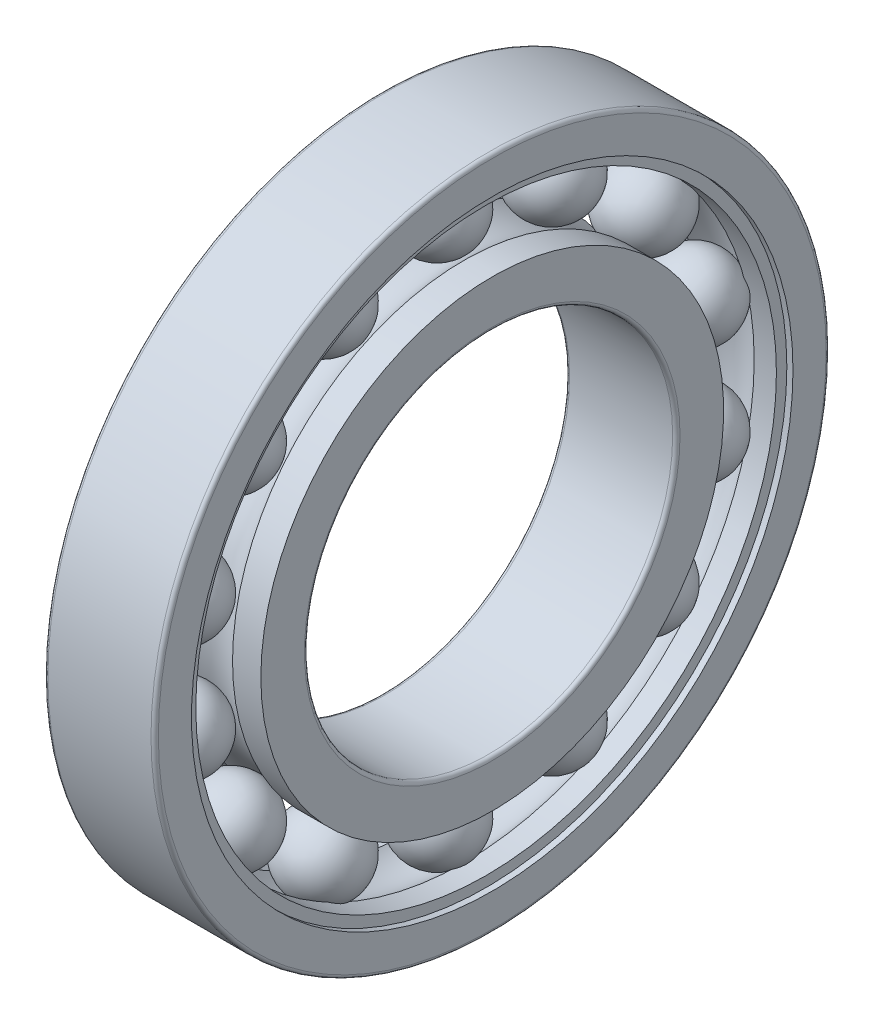
SolidWorks part; units mm, degrees
ref_plane "Front Plane" through (0, 0, 0) normal (0, 0, 1) x (1, 0, 0)
ref_plane "Top Plane" through (0, 0, 0) normal (0, 1, 0) x (1, 0, 0)
ref_plane "Right Plane" through (0, 0, 0) normal (1, 0, 0) x (0, 0, -1)
sketch "Sketch1" plane through (0, 0, 0) normal (0, 0, 1) x (1, 0, 0)
  line L0 (0, 0) -> (0, 25.575) construction
  line L9 (0, 0) -> (12.2235, 0) construction
  line L10 (-2.8431, 23.65) -> (-2.8431, 18.85) construction
  line L11 (4.5, 27.5) -> (-4.5, 27.5)
  line L12 (4.5, 27.5) -> (4.5, 23.65)
  line L13 (4.5, 23.65) -> (-4.5, 23.65)
  line L14 (-4.5, 27.5) -> (-4.5, 23.65)
  line L15 (4.5, 27.5) -> (-4.5, 23.65) construction
  line L16 (4.5, 23.65) -> (-4.5, 27.5) construction
  line L17 (4.5, 18.85) -> (-4.5, 18.85)
  line L18 (4.5, 18.85) -> (4.5, 15)
  line L19 (4.5, 15) -> (-4.5, 15)
  line L20 (-4.5, 18.85) -> (-4.5, 15)
  line L21 (4.5, 18.85) -> (-4.5, 15) construction
  line L22 (4.5, 15) -> (-4.5, 18.85) construction
  line L23 (-2.8431, 21.25) -> (0, 21.25) construction
  circle A0 centre (0, 21.25) radius 3.25
  point P7 (0, 16.925)
  dimension "D6" = 6.5
  dimension "D1" = 15
  dimension "D2" = 18.85
  dimension "D3" = 23.65
  dimension "D4" = 27.5
  dimension "D5" = 9
revolve "Revolve1" add sketch "Sketch1" angle 360 about L9
sketch "Sketch2" plane through (4.5, 0, 0) normal (1, 0, 0) x (0, 0, -1)
  circle A0 centre (0, 0) radius 24.5
  circle A1 centre (0, 0) radius 23.65 construction
  circle A2 centre (0, 0) radius 23.65
  dimension "D1" = 49
extrude "Cut-Extrude1" cut sketch "Sketch2" against normal blind 0.5
mirror "Mirror1" about plane through (0, 0, 0) normal (1, 0, 0) of "Cut-Extrude1"
fillet "Fillet1" radius 0.3 2 edges at (-4.5, 0, 27.5) (4.5, 0, 27.5)
fillet "Fillet2" radius 0.3 2 edges at (-4.5, 0, 15) (4.5, 0, 15)
sketch "Sketch3" plane through (0, 0, 0) normal (0, 0, 1) x (1, 0, 0)
  line L0 (-3.225, 21.5) -> (3.225, 21.5)
  arc A0 (3.225, 21.5) -> (-3.225, 21.5) centre (0, 21.5) ccw
  dimension "D1" = 6.45
  dimension "D2" = 21.5
revolve "Revolve2" add sketch "Sketch3" angle 360 about L0
pattern_circular "CirPattern4" count 14 over 360 about axis through (0, 0, 0) along (1, 0, 0) of bodies 105
